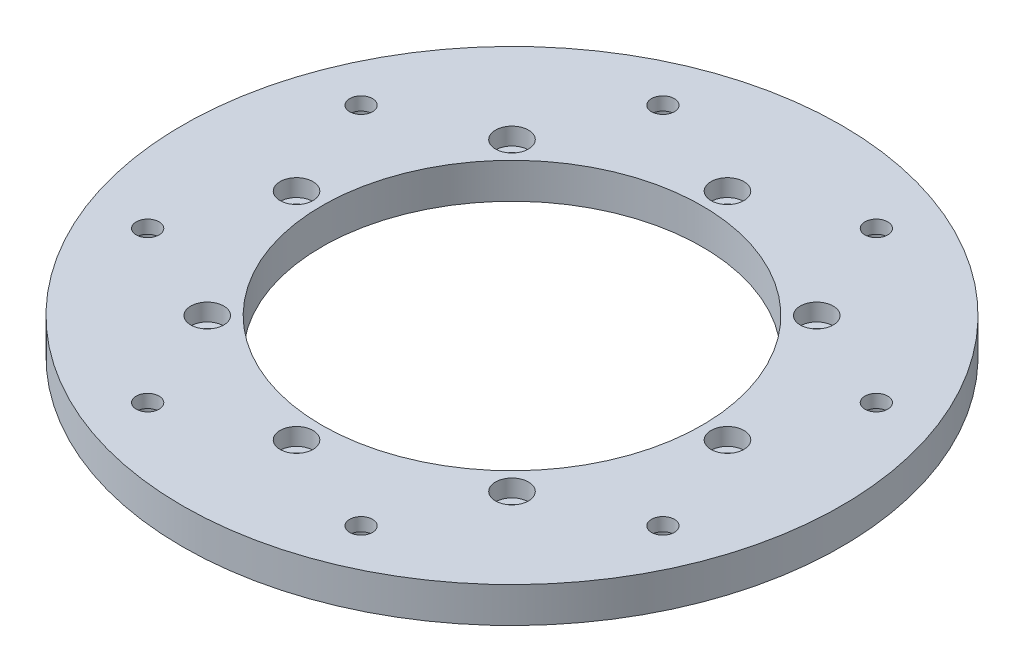
SolidWorks part; units mm, degrees
material "6061-T6 (SS)"
ref_plane "Front Plane" through (0, 0, 0) normal (0, 0, 1) x (1, 0, 0)
ref_plane "Top Plane" through (0, 0, 0) normal (0, 1, 0) x (1, 0, 0)
ref_plane "Right Plane" through (0, 0, 0) normal (1, 0, 0) x (0, 0, -1)
sketch "Sketch1" plane through (0, 0, 0) normal (0, 1, 0) x (1, 0, 0)
  circle A0 centre (0, 0) radius 37.5
  circle A1 centre (0, 0) radius 65
  dimension "D1" = 75
  dimension "D2" = 130
extrude "Boss-Extrude1" add sketch "Sketch1" along normal blind 7
sketch "Sketch4" plane through (0, 7, 0) normal (0, 1, 0) x (1, 0, 0)
  circle A0 centre (0, 0) radius 42.5 construction
  point P4 (0, 42.5)
  point P13 (30.052, 30.052)
  point P14 (42.5, 0)
  point P15 (30.052, -30.052)
  point P16 (0, -42.5)
  point P17 (-30.052, -30.052)
  point P18 (-42.5, 0)
  point P19 (-30.052, 30.052)
  dimension "D1" = 85
  dimension "D2" = 8
hole_wizard "CBORE for M3 Hex Socket Head Cap Screw1" positions "Sketch4" profile "Sketch3" counterbore size "M3" standard "DIN" end condition through all
sketch "Sketch3" plane through (-30.052, 7, -30.052) normal (1, 0, 0) x (0, 0, 1)
  line L0 (0, 0) -> (0, 7)
  line L1 (0, 7) -> (1.7, 7)
  line L3 (1.7, 7) -> (1.7, 3.4)
  line L4 (1.7, 3.4) -> (3.25, 3.4)
  line L5 (3.25, 3.4) -> (3.25, 0)
  line L7 (3.25, 0) -> (0, 0)
  line L11 (0, -6.35) -> (0, 107.95) construction
  dimension "Thru Hole Dia." = 3.4
  dimension "Thru Hole Depth" = 7
  dimension "C'Bore Dia." = 6.5
  dimension "C'Bore Depth" = 3.4
sketch "Sketch7" plane through (0, 0, 0) normal (0, -1, 0) x (-1, 0, 0)
  line L0 (0, 0) -> (-61.0389, 25.2831) construction
  circle A0 centre (0, 0) radius 55
  point P9 (-50.8134, 21.0476)
  point P17 (-21.0476, 50.8134)
  point P18 (21.0476, 50.8134)
  point P19 (50.8134, 21.0476)
  point P20 (50.8134, -21.0476)
  point P21 (21.0476, -50.8134)
  point P22 (-21.0476, -50.8134)
  point P23 (-50.8134, -21.0476)
  dimension "D1" = 22.5
  dimension "D2" = 110
  dimension "D3" = 8
hole_wizard "CBORE for M4 Hex Socket Head Cap Screw1" positions "Sketch7" profile "Sketch6" counterbore size "M4" standard "DIN" end condition through all
sketch "Sketch6" plane through (50.8134, 0, 21.0476) normal (1, 0, 0) x (0, 0, -1)
  line L0 (0, 0) -> (0, 7)
  line L1 (0, 7) -> (2.25, 7)
  line L3 (2.25, 7) -> (2.25, 4.4)
  line L4 (2.25, 4.4) -> (4, 4.4)
  line L5 (4, 4.4) -> (4, 0)
  line L7 (4, 0) -> (0, 0)
  line L11 (0, -6.35) -> (0, 107.95) construction
  dimension "Thru Hole Dia." = 4.5
  dimension "Thru Hole Depth" = 7
  dimension "C'Bore Dia." = 8
  dimension "C'Bore Depth" = 4.4
